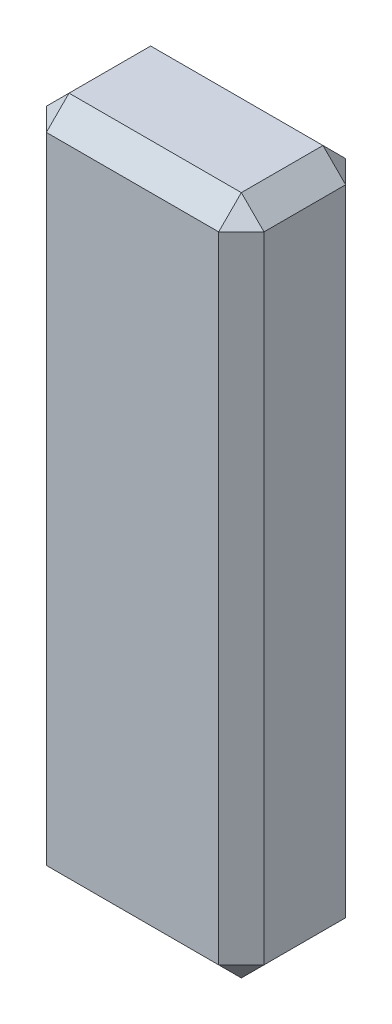
SolidWorks part; units mm, degrees
ref_plane "Front" through (0, 0, 0) normal (0, 0, 1) x (1, 0, 0)
ref_plane "Top" through (0, 0, 0) normal (0, 1, 0) x (1, 0, 0)
ref_plane "Right" through (0, 0, 0) normal (1, 0, 0) x (0, 0, -1)
sketch "Sketch1" plane through (0, 0, 0) normal (0, 1, 0) x (1, 0, 0)
  line L1 (-2.4, -1.4) -> (2.4, -1.4)
  line L2 (-2.4, -1.4) -> (-2.4, 1.4)
  line L3 (-2.4, 1.4) -> (2.4, 1.4)
  line L4 (2.4, -1.4) -> (2.4, 1.4)
  line L5 (-2.4, -1.4) -> (2.4, 1.4) construction
  line L6 (-2.4, 1.4) -> (2.4, -1.4) construction
  point P0 (0, 0)
extrude "Boss-Extrude1" add sketch "Sketch1" along normal blind 15
chamfer "Chamfer1" distance 0.5 angle 45 12 edges at (-2.4, 0, 0) (2.4, 0, 0) (-2.4, 15, 0) (-2.4, 7.5, 1.4) (0, 15, 1.4) (0, 0, 1.4) (2.4, 7.5, 1.4) (2.4, 15, 0) (2.4, 7.5, -1.4) (0, 15, -1.4) (-2.4, 7.5, -1.4) (0, 0, -1.4)
